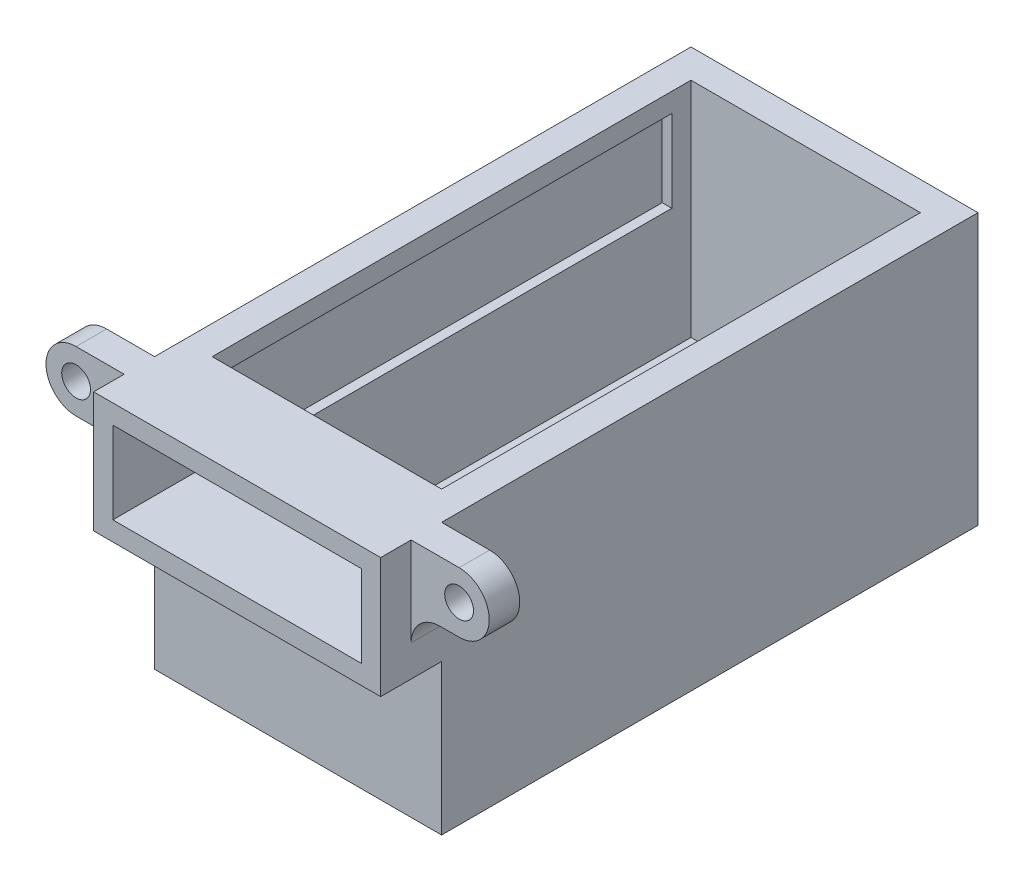
SolidWorks part; units mm, degrees
ref_plane "Front Plane" through (0, 0, 0) normal (0, 0, 1) x (1, 0, 0)
ref_plane "Top Plane" through (0, 0, 0) normal (0, 1, 0) x (1, 0, 0)
ref_plane "Right Plane" through (0, 0, 0) normal (1, 0, 0) x (0, 0, -1)
sketch "Sketch1" plane through (0, 0, 0) normal (0, 0, 1) x (1, 0, 0)
  line L0 (0, 0) -> (0, 12.55)
  line L1 (0, 12.55) -> (29.9, 12.55)
  line L2 (29.9, 12.55) -> (29.9, 0)
  line L3 (29.9, 0) -> (0, 0)
  line L4 (0, 6.275) -> (-5, 6.275)
  line L5 (0, 12.55) -> (-5, 12.55)
  line L6 (29.9, 6.275) -> (34.9, 6.275)
  line L7 (29.9, 12.55) -> (34.9, 12.55)
  arc A0 (-5, 12.55) -> (-5, 6.275) centre (-5, 9.4125) ccw
  arc A1 (34.9, 12.55) -> (34.9, 6.275) centre (34.9, 9.4125) cw
  circle A2 centre (-5, 9.4125) radius 1.5
  circle A3 centre (34.9, 9.4125) radius 1.5
  dimension "D1" = 12.55
  dimension "D5" = 3
  dimension "D6" = 3
  dimension "D2" = 29.9
  dimension "D3" = 5
  dimension "D4" = 5
extrude "Boss-Extrude1" add sketch "Sketch1" along normal blind 3.175 contours L3 L2 L1 L0 | L5 A0 L4 L0 A2 | A1 L7 L2 L6 A3
sketch "Sketch2" plane through (0, 0, 3.175) normal (0, 0, 1) x (1, 0, 0)
  line L0 (0, 0) -> (0, 12.55)
  line L1 (-5, 12.55) -> (34.9, 12.55) construction
  line L2 (0, 0) -> (29.9, 0)
  line L3 (29.9, 0) -> (29.9, 12.55)
  line L4 (29.9, 12.55) -> (0, 12.55)
extrude "Boss-Extrude2" add sketch "Sketch2" along normal blind 3.175
sketch "Sketch3" plane through (0, 0, 0) normal (0, 0, -1) x (-1, 0, 0)
  line L0 (-29.9, 0) -> (-29.9, -15.661)
  line L1 (-29.9, -15.661) -> (0, -15.661)
  line L2 (0, -15.661) -> (0, 12.55)
  line L3 (5, 12.55) -> (-34.9, 12.55) construction
  line L4 (0, 12.55) -> (-29.9, 12.55)
  line L5 (-29.9, 12.55) -> (-29.9, 0)
  dimension "D1" = 15.661
extrude "Boss-Extrude3" add sketch "Sketch3" along normal blind 55.88
sketch "Sketch5" plane through (0, 0, 3.175) normal (0, 0, 1) x (1, 0, 0)
  line L0 (29.9, 6.275) -> (34.9, 6.275) construction
  line L1 (29.9, 0) -> (29.9, 12.55) construction
  line L2 (29.9, 6.275) -> (32.9, 6.275)
  line L3 (29.9, 6.275) -> (29.9, 3.275)
  line L4 (29.9, 6.275) -> (0, 6.275) construction
  line L5 (14.95, 6.275) -> (14.95, 12.55) construction
  line L6 (29.9, 12.55) -> (34.9, 12.55) construction
  line L7 (0, 6.275) -> (-3, 6.275)
  line L8 (0, 6.275) -> (0, 3.275)
  circle A0 centre (32.9, 3.275) radius 3
  arc A1 (32.9, 6.275) -> (29.9, 3.275) centre (32.9, 3.275) ccw
  arc A2 (-3, 6.275) -> (0, 3.275) centre (-3, 3.275) cw
  line M3 (29.9, 6.275) -> (34.9, 6.275)
  dimension "D1" = 6
extrude "Boss-Extrude4" add sketch "Sketch5" against normal up to surface (3.175 mm away) contours A0 L3 M3 | L7 A2 L8 up to face at (36.4, 9.4125, 0)
sketch "Sketch6" plane through (0, 0, 6.35) normal (0, 0, 1) x (1, 0, 0)
  line L0 (2, 2) -> (2, 10.55)
  line L1 (2, 10.55) -> (27.9, 10.55)
  line L2 (27.9, 10.55) -> (27.9, 2)
  line L3 (27.9, 2) -> (2, 2)
  line L4 (0, 12.55) -> (0, 0) construction
  line L5 (29.9, 0) -> (29.9, 12.55) construction
  line L6 (0, 0) -> (29.9, 0) construction
  line L7 (29.9, 12.55) -> (0, 12.55) construction
  dimension "D1" = 2
  dimension "D2" = 2
  dimension "D3" = 2
  dimension "D4" = 2
extrude "Cut-Extrude1" cut sketch "Sketch6" against normal offset from surface (57.23 mm away) 5 up to face at (14.95, -1.5555, -55.88)
sketch "Sketch7" plane through (0, 12.55, 0) normal (0, 1, 0) x (1, 0, 0)
  line L0 (26.9, 52.88) -> (3, 52.88)
  line L1 (3, 52.88) -> (3, 3)
  line L2 (3, 3) -> (26.9, 3)
  line L3 (26.9, 3) -> (26.9, 52.88)
  line L4 (0, 55.88) -> (29.9, 55.88) construction
  line L5 (0, 55.88) -> (0, 0) construction
  line L6 (29.9, 55.88) -> (29.9, 0) construction
  line L7 (29.9, 0) -> (34.9, 0) construction
  dimension "D1" = 3
  dimension "D2" = 3
  dimension "D3" = 3
  dimension "D4" = 3
extrude "Cut-Extrude2" cut sketch "Sketch7" against normal offset from surface (23.211 mm away) 5 up to face at (14.95, -15.661, -27.94)
equation "\"wall_thickness\"= 0.125in"
equation "\"base_thickness\"= 0.25in"
equation "\"D1@Boss-Extrude1\"=\"wall_thickness\""
equation "\"D1@Boss-Extrude2\"=\"wall_thickness\""
